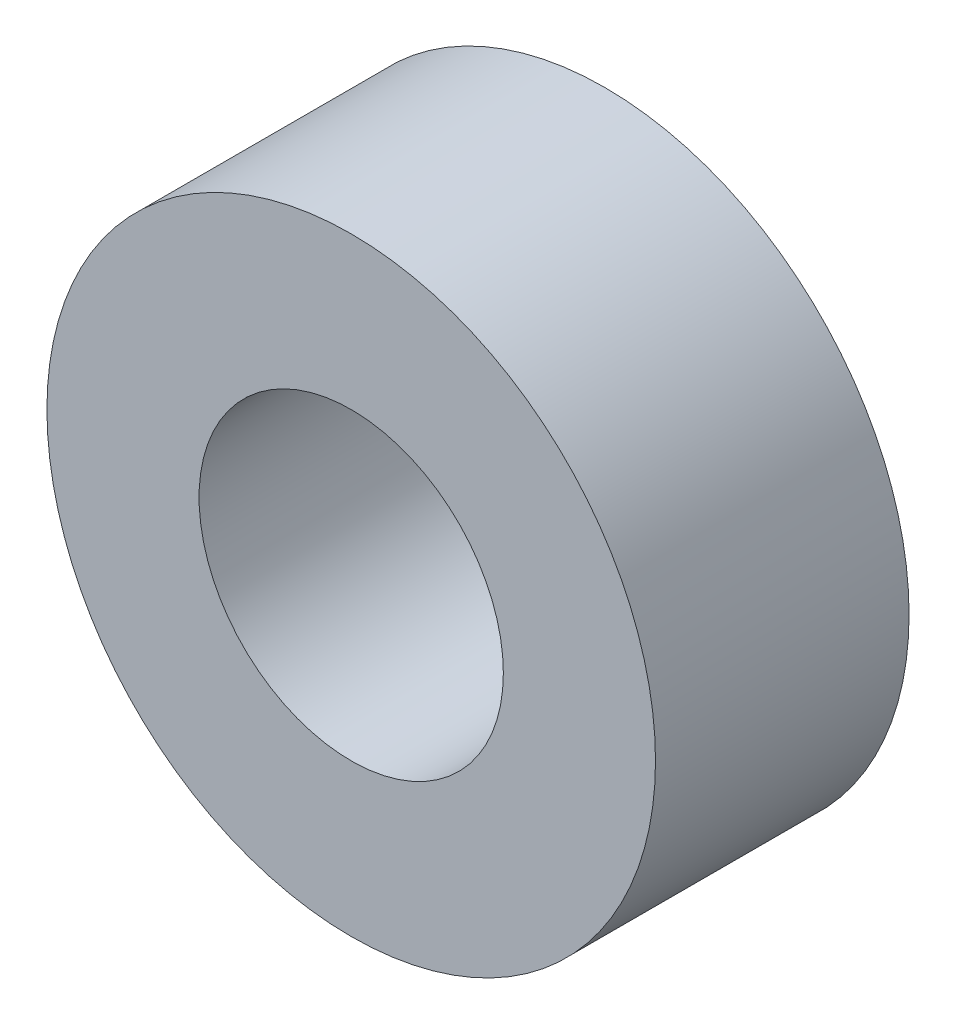
SolidWorks part; units mm, degrees
ref_plane "Front Plane" through (0, 0, 0) normal (0, 0, 1) x (1, 0, 0)
ref_plane "Top Plane" through (0, 0, 0) normal (0, 1, 0) x (1, 0, 0)
ref_plane "Right Plane" through (0, 0, 0) normal (1, 0, 0) x (0, 0, -1)
sketch "Sketch1" plane through (0, 0, 0) normal (0, 0, 1) x (1, 0, 0)
  circle A0 centre (0, 0) radius 3
  circle A1 centre (0, 0) radius 1.5
  dimension "D1" = 6
  dimension "D2" = 3
extrude "Boss-Extrude1" add sketch "Sketch1" against normal blind 2.5
